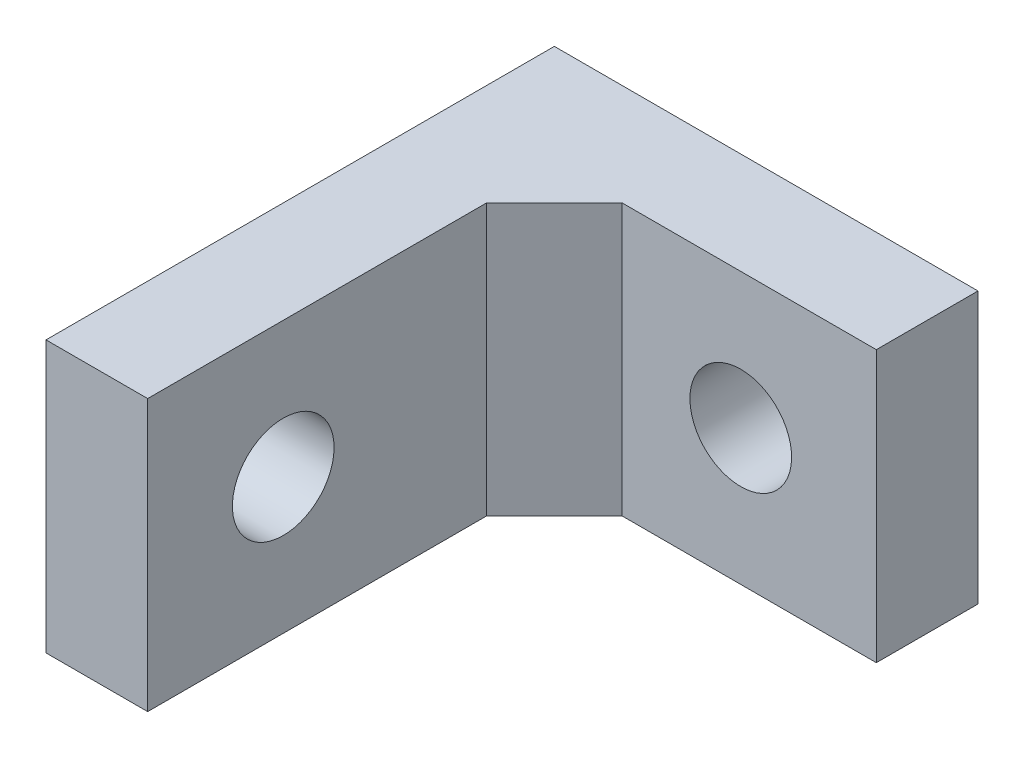
SolidWorks part; units mm, degrees
ref_plane "Front Plane" through (0, 0, 0) normal (0, 0, 1) x (1, 0, 0)
ref_plane "Top Plane" through (0, 0, 0) normal (0, 1, 0) x (1, 0, 0)
ref_plane "Right Plane" through (0, 0, 0) normal (1, 0, 0) x (0, 0, -1)
sketch "Sketch1" plane through (0, 0, 0) normal (1, 0, 0) x (0, 0, -1)
  line L1 (0, 0) -> (15, 0)
  line L2 (0, 0) -> (0, -8)
  line L3 (0, -8) -> (15, -8)
  line L4 (15, 0) -> (15, -8)
  circle A0 centre (4, -4) radius 1.5
  dimension "D3" = 3
  dimension "D4" = 4
  dimension "D5" = 4
  dimension "D1" = 15
  dimension "D2" = 8
extrude "Boss-Extrude1" add sketch "Sketch1" along normal blind 3
sketch "Sketch2" plane through (0, 0, -15) normal (0, 0, -1) x (-1, 0, 0)
  line L1 (0, 0) -> (-12.5, 0)
  line L2 (0, 0) -> (0, -8)
  line L3 (0, -8) -> (-12.5, -8)
  line L4 (-12.5, 0) -> (-12.5, -8)
  circle A0 centre (-8.5, -4) radius 1.5
  dimension "D2" = 3
  dimension "D3" = 4
  dimension "D1" = 12.5
extrude "Boss-Extrude2" add sketch "Sketch2" against normal blind 3
chamfer "Chamfer1" distance 2 angle 45 1 edges at (3, -4, -12)
